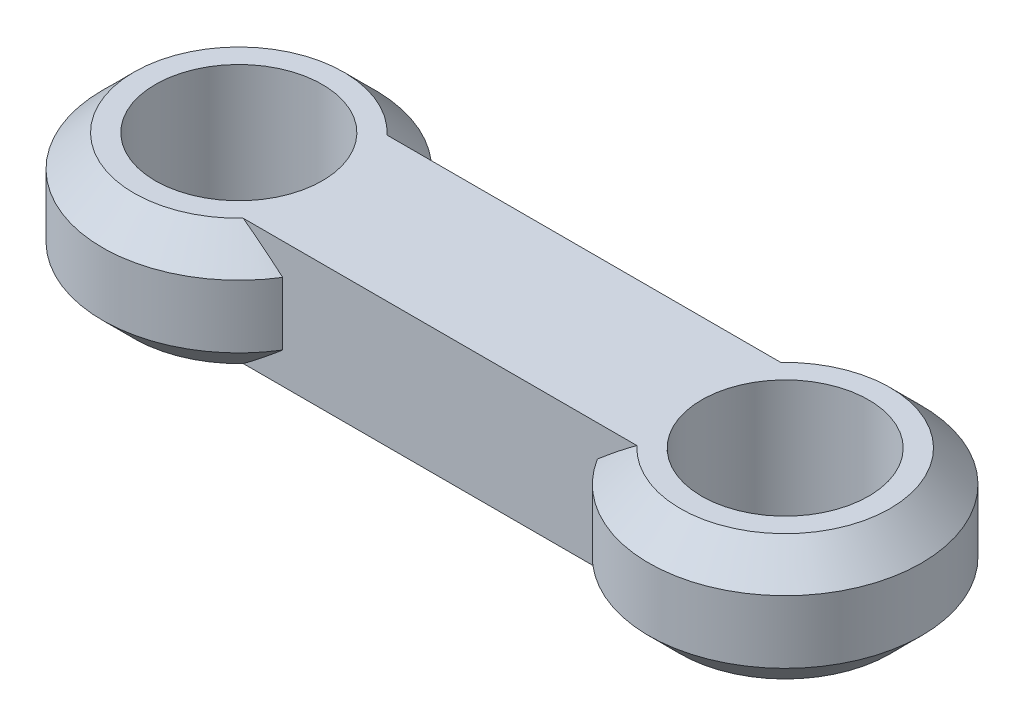
SolidWorks part; units mm, degrees
ref_plane "Front Plane" through (0, 0, 0) normal (0, 0, 1) x (1, 0, 0)
ref_plane "Top Plane" through (0, 0, 0) normal (0, 1, 0) x (1, 0, 0)
ref_plane "Right Plane" through (0, 0, 0) normal (1, 0, 0) x (0, 0, -1)
sketch "Sketch1" plane through (0, 0, 0) normal (0, 1, 0) x (1, 0, 0)
  line L0 (0, 0) -> (-26.0425, 0) construction
  line L1 (-5.5213, 3.4301) -> (-20.5213, 3.4301)
  line L2 (-5.5213, -3.4301) -> (-20.5213, -3.4301)
  circle A0 centre (0, 0) radius 3.98
  circle A1 centre (0, 0) radius 6.5
  circle A2 centre (-26.0425, 0) radius 3.98
  circle A3 centre (-26.0425, 0) radius 6.5
  dimension "D1" = 7.96
  dimension "D2" = 13
  dimension "D3" = 15
extrude "Boss-Extrude1" add sketch "Sketch1" along normal blind 6
chamfer "Chamfer1" distance 1.5 angle 45 4 edges at (6.5, 0, 0) (-32.5425, 0, 0) (6.5, 6, 0) (-32.5425, 6, 0)
